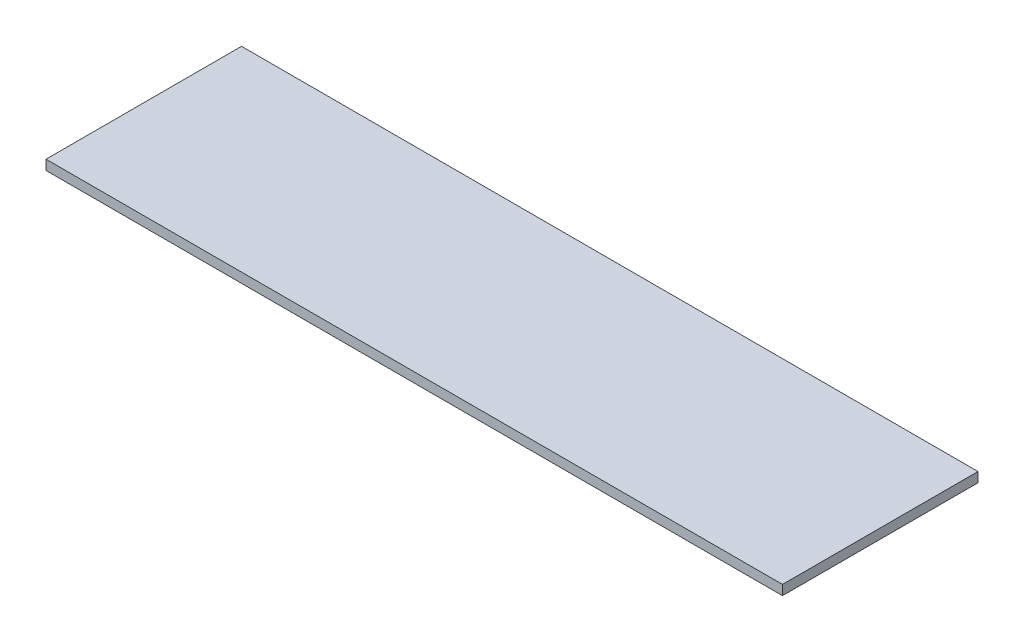
SolidWorks part; units mm, degrees
ref_plane "前视基准面" through (0, 0, 0) normal (0, 0, 1) x (1, 0, 0)
ref_plane "上视基准面" through (0, 0, 0) normal (0, 1, 0) x (1, 0, 0)
ref_plane "右视基准面" through (0, 0, 0) normal (1, 0, 0) x (0, 0, -1)
sketch "草图1" plane through (0, 0, 0) normal (0, 1, 0) x (1, 0, 0)
  line L1 (0, 0) -> (226, 0)
  line L2 (0, 0) -> (0, -60)
  line L3 (0, -60) -> (226, -60)
  line L4 (226, 0) -> (226, -60)
  dimension "D1" = 226
  dimension "D2" = 60
extrude "凸台-拉伸1" add sketch "草图1" along normal blind 3
